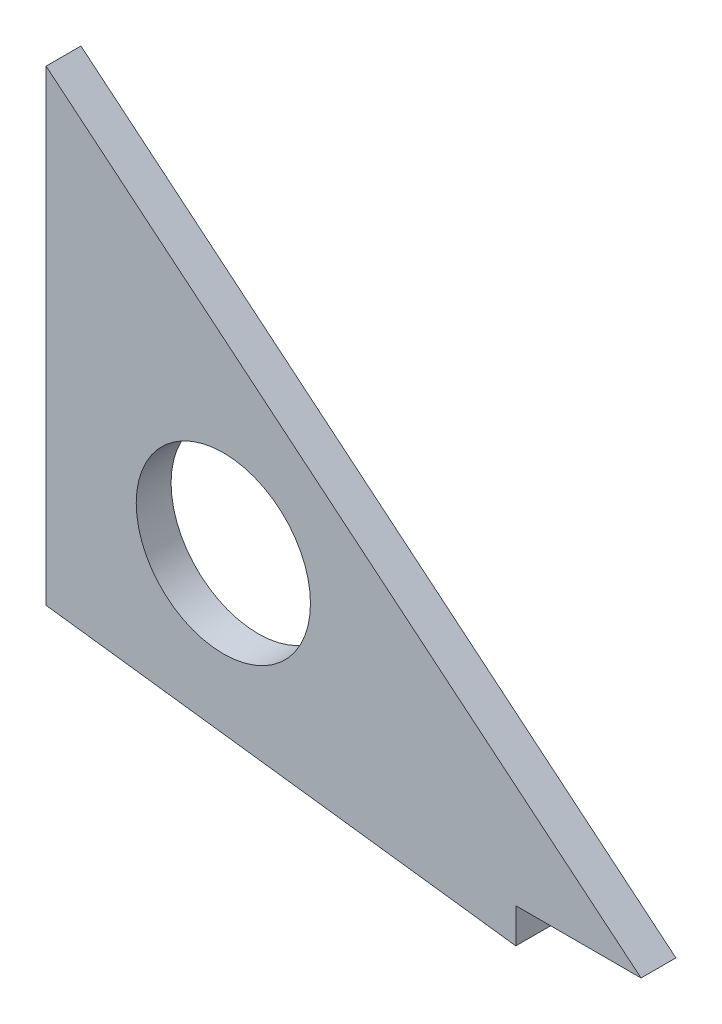
SolidWorks part; units mm, degrees
ref_plane "前视基准面" through (0, 0, 0) normal (0, 0, 1) x (1, 0, 0)
ref_plane "上视基准面" through (0, 0, 0) normal (0, 1, 0) x (1, 0, 0)
ref_plane "右视基准面" through (0, 0, 0) normal (1, 0, 0) x (0, 0, -1)
sketch "Model" plane through (0, 0, 0) normal (0, 0, 1) x (1, 0, 0)
  line L0 (24.8749, 9.6454) -> (24.8749, 36.4485)
  line L1 (51.8329, 8.1971) -> (59.0224, 8.1971)
  line L2 (24.8749, 36.4485) -> (59.0224, 8.1971)
  line L3 (51.8329, 6.1971) -> (51.8329, 8.1971)
  line L4 (24.8749, 9.6454) -> (51.8329, 6.1971)
  circle A0 centre (35.0478, 17.3204) radius 5
extrude "凸台-拉伸1" add sketch "Model" along normal blind 2
